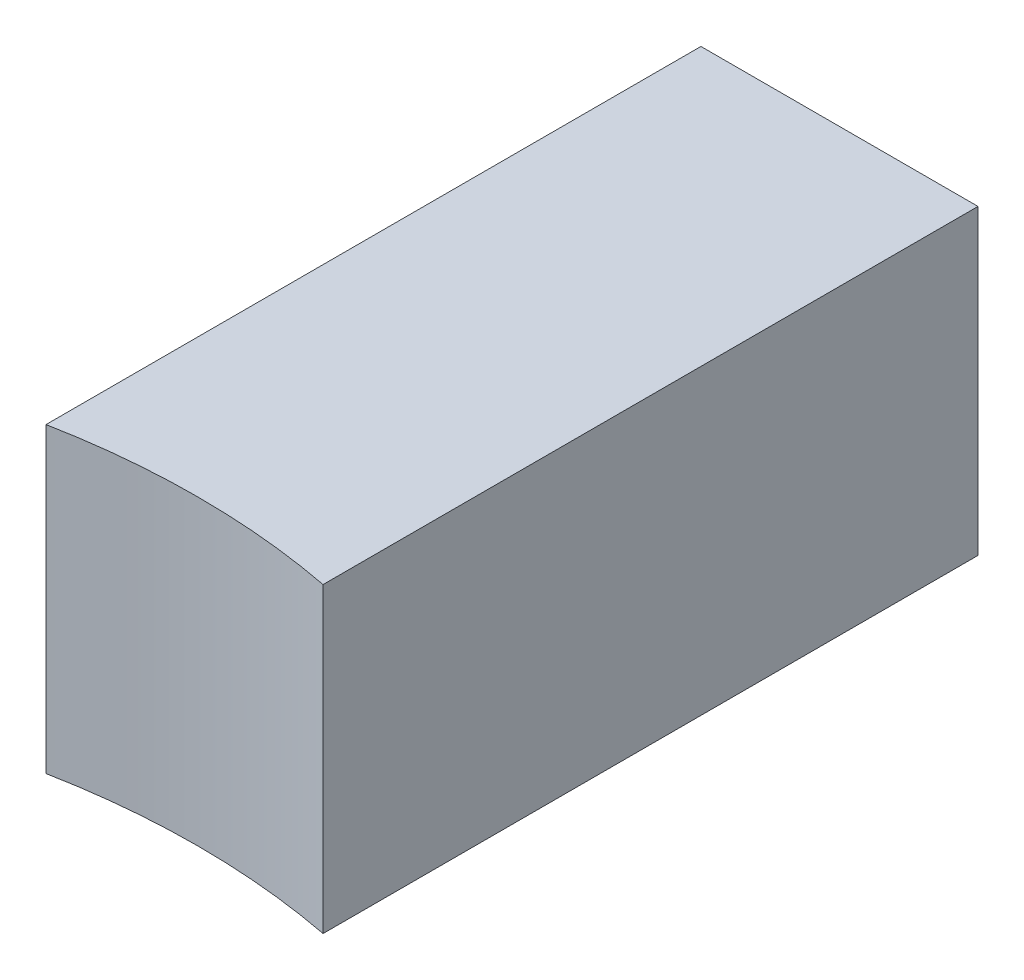
SolidWorks part; units mm, degrees
ref_plane "Plan de face" through (0, 0, 0) normal (0, 0, 1) x (1, 0, 0)
ref_plane "Plan de dessus" through (0, 0, 0) normal (0, 1, 0) x (1, 0, 0)
ref_plane "Plan de droite" through (0, 0, 0) normal (1, 0, 0) x (0, 0, -1)
sketch "Esquisse1" plane through (0, 0, 0) normal (0, 1, 0) x (1, 0, 0)
  line L1 (-2.75, 27.2368) -> (2.75, 27.2368)
  line L2 (-2.75, 27.2368) -> (-2.75, 14.2368)
  line L4 (2.75, 27.2368) -> (2.75, 14.2368)
  arc A0 (2.75, 14.2368) -> (-2.75, 14.2368) centre (0, 0) ccw
  dimension "D1" = 29
  dimension "D2" = 5.5
  dimension "D3" = 13
extrude "Boss.-Extru.1" add sketch "Esquisse1" against normal blind 6
